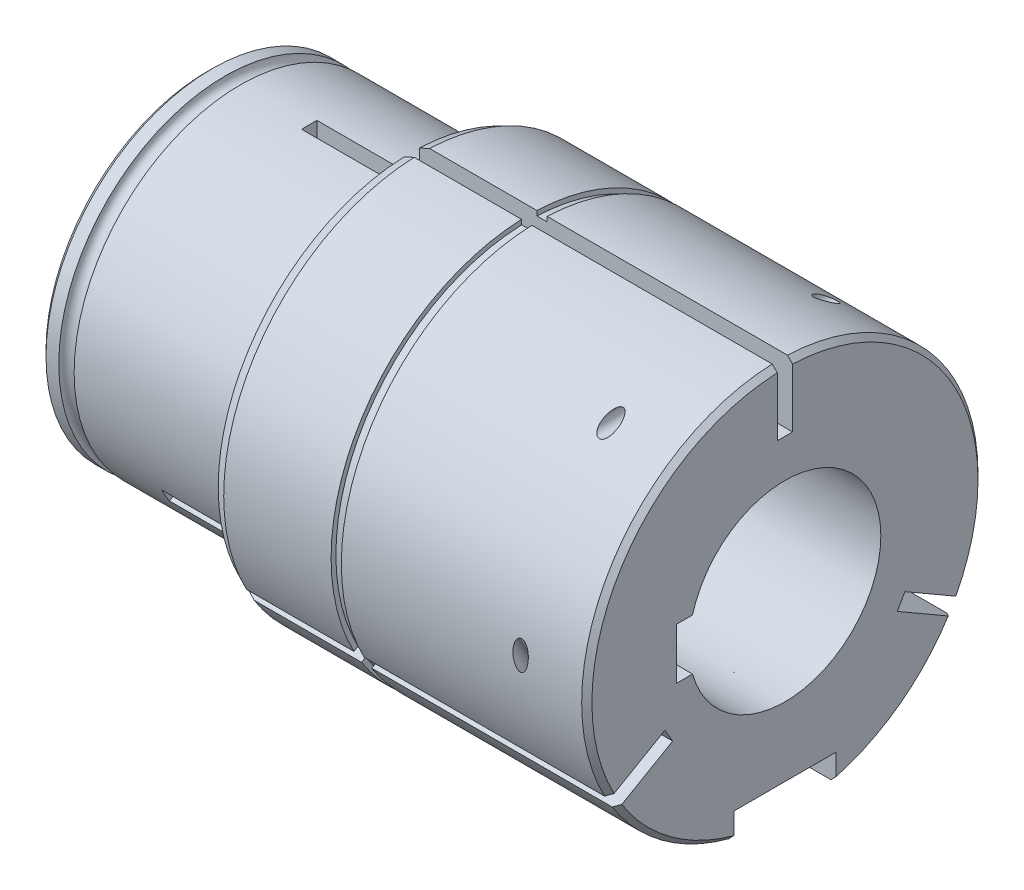
SolidWorks part; units mm, degrees
ref_plane "Спереди" through (0, 0, 0) normal (0, 0, 1) x (1, 0, 0)
ref_plane "Сверху" through (0, 0, 0) normal (0, 1, 0) x (1, 0, 0)
ref_plane "Справа" through (0, 0, 0) normal (1, 0, 0) x (0, 0, -1)
sketch "Эскиз1" plane through (0, 0, 0) normal (0, 0, 1) x (1, 0, 0)
  line L0 (-97.05, 0) -> (115.95, 0) construction
  line L1 (-75.6561, 45) -> (4.3439, 45)
  line L2 (4.3439, 45) -> (4.3439, 37.5)
  line L3 (4.3439, 37.5) -> (150.3439, 37.5)
  line L4 (150.3439, 37.5) -> (150.3439, 77.5)
  line L5 (150.3439, 77.5) -> (54.3439, 77.5)
  line L6 (4.3439, 75.6348) -> (4.3439, 65)
  line L7 (4.3439, 65) -> (-62.6561, 65)
  line L8 (-75.6561, 45) -> (-75.6561, 65)
  line L9 (4.3439, 75.6348) -> (8.3439, 77.5)
  line L10 (-68.6561, 65) -> (-75.6561, 65)
  line L11 (50.3439, 77.5) -> (50.3439, 75.6348)
  line L12 (50.3439, 75.6348) -> (54.3439, 75.6348)
  line L13 (54.3439, 75.6348) -> (54.3439, 77.5)
  line L14 (50.3439, 77.5) -> (8.3439, 77.5)
  arc A0 (-68.6561, 65) -> (-62.6561, 65) centre (-65.6561, 65) ccw
  dimension "D7" = 6
  dimension "D1" = 75
  dimension "D2" = 90
  dimension "D3" = 226
  dimension "D4" = 80
  dimension "D5" = 155
  dimension "D6" = 130
  dimension "D8" = 10
  dimension "D9" = 4
  dimension "D10" = 65
  dimension "D11" = 4
  dimension "D12" = 130
revolve "Повернуть1" add sketch "Эскиз1" angle 360 about L0
chamfer "Фаска1" distance 2 angle 45 3 edges at (4.3439, 0, 37.5) (-75.6561, 0, 65) (150.3439, 0, 77.5)
sketch "Эскиз2" plane through (150.3439, 0, 0) normal (1, 0, 0) x (0, 0, -1)
  line L0 (0, 101.971) -> (0, -95.8712) construction
  line L1 (-3, 77.4419) -> (-3, 78.906)
  line L2 (-3, 77.4419) -> (-3, 52.4419)
  line L3 (-3, 52.4419) -> (3, 52.4419)
  line L4 (3, 52.4419) -> (3, 77.4419)
  line L6 (-3, 78.906) -> (3, 78.906)
  line L7 (3, 78.906) -> (3, 77.4419)
  circle A0 centre (0, 0) radius 77.5 construction
  dimension "D3" = 155
  dimension "D1" = 6
extrude "Вырез-Вытянуть1" cut sketch "Эскиз2" against normal blind 186
fillet "Скругление1" radius 5 1 edges at (-35.6561, 52.4419, 0)
pattern_circular "Круговой массив1" count 3 over 360 about axis through (0, 0, 0) along (1, 0, 0) of "Вырез-Вытянуть1", "Скругление1"
sketch "Эскиз3" plane through (0, 0, 0) normal (0, 0, 1) x (1, 0, 0)
  line L0 (-122.0129, 0) -> (174.9116, 0) construction
  line L1 (150.3439, 52.4419) -> (150.3439, 75.4404) construction
  line L2 (-30.6561, 52.4419) -> (150.3439, 52.4419) construction
  circle A0 centre (124.3439, 64.9419) radius 3
  dimension "D3" = 6
  dimension "D1" = 26
  dimension "D2" = 12.5
extrude "Вырез-Вытянуть2" cut sketch "Эскиз3" against normal through all both and the other way through all
pattern_circular "Круговой массив2" count 3 over 360 about axis through (148.3439, 0, 0) along (-1, 0, 0) of "Вырез-Вытянуть2"
sketch "Эскиз4" plane through (150.3439, 0, 0) normal (1, 0, 0) x (0, 0, -1)
  line L0 (37.5, 0) -> (37.5, 41.1878) construction
  line L1 (65.4504, 0) -> (-58.3819, 0) construction
  line L2 (-28.7053, 10) -> (-42.4, 10)
  line L3 (-42.4, 10) -> (-42.4, -10)
  line L4 (-42.4, -10) -> (-28.7053, -10)
  line L5 (-28.7053, -10) -> (-28.7053, 10)
  line L6 (0, 27.8161) -> (0, -18.7707) construction
  circle A0 centre (0, 0) radius 37.5 construction
  dimension "D1" = 20
  dimension "D2" = 79.9
extrude "Вырез-Вытянуть3" cut sketch "Эскиз4" against normal blind 146
sketch "Эскиз5" plane through (150.3439, 0, 0) normal (1, 0, 0) x (0, 0, -1)
  line L0 (0, 90.7985) -> (0, -98.7204) construction
  line L1 (-143.3187, 0) -> (122.0863, 0) construction
  line L2 (-20, -86.1382) -> (-20, -64.5)
  line L3 (-20, -64.5) -> (20, -64.5)
  line L4 (20, -64.5) -> (20, -86.1382)
  line L5 (20, -86.1382) -> (-20, -86.1382)
  line L6 (0, 77.5) -> (-85.1262, 77.5) construction
  circle A0 centre (0, 0) radius 77.5 construction
  dimension "D1" = 40
  dimension "D2" = 142
extrude "Вырез-Вытянуть4" cut sketch "Эскиз5" against normal blind 146
sketch "Эскиз6" plane through (0, -64.5, 0) normal (0, -1, 0) x (1, 0, 0)
  line L0 (150.3439, -20) -> (150.3439, 20) construction
  circle A0 centre (130.3439, 0) radius 5.3379
  circle A1 centre (70.3439, 0) radius 8.0912
  dimension "D1" = 20
  dimension "D2" = 60
hole_wizard "Отверстие обработанное метчиком M121" positions "Эскиз7" profile "Эскиз8" tap size "M12" standard "ISO"
sketch "Эскиз7" plane through (0, -64.5, 0) normal (0, -1, 0) x (-1, 0, 0)
  point P0 (-70.3439, 0)
  point P3 (-130.3439, 0)
sketch "Эскиз8" plane through (70.3439, -64.5, 0) normal (1, 0, 0) x (0, 0, -1)
  line L0 (0, 0) -> (0, 27.0644)
  line L1 (0, 27.0644) -> (5.1, 24)
  line L2 (5.1, 24) -> (5.1, 0)
  line L5 (5.1, 0) -> (0, 0)
  line L10 (0, 27.0644) -> (-5.1, 24) construction
  line L11 (0, -6.35) -> (0, 107.95) construction
  dimension "Диаметр сверла" = 10.2
  dimension "Глубина сверла" = 24
  dimension "Угол заточки сверла" = 118
cosmetic thread "Отверстие резьбы1" parameters "D1"=18, "D2"=12
cosmetic thread "Отверстие резьбы2" parameters "D1"=18, "D2"=12
